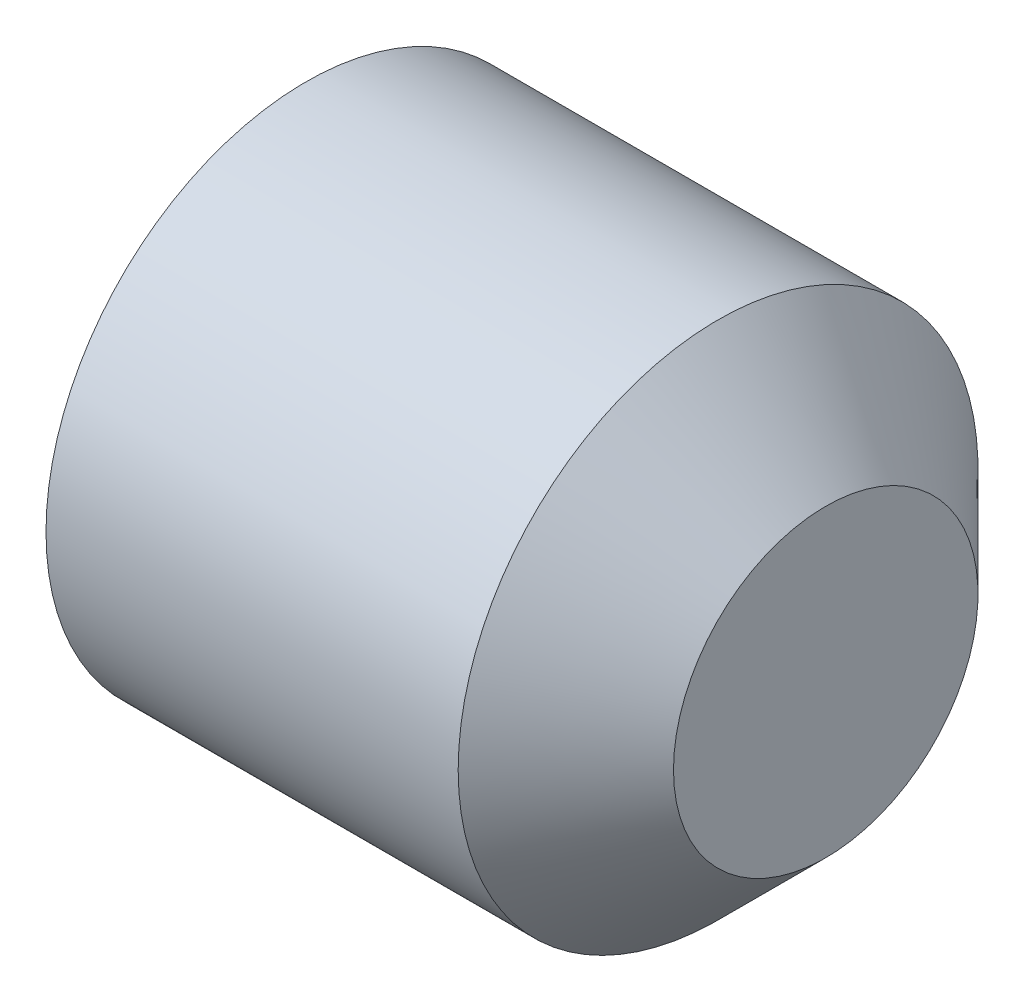
SolidWorks part; units mm, degrees
material "AISI 304"
ref_plane "Front Plane" through (0, 0, 0) normal (0, 0, 1) x (1, 0, 0)
ref_plane "Top Plane" through (0, 0, 0) normal (0, 1, 0) x (1, 0, 0)
ref_plane "Right Plane" through (0, 0, 0) normal (1, 0, 0) x (0, 0, -1)
sketch "Sketch1" plane through (0, 0, 0) normal (0, 0, 1) x (1, 0, 0)
  line L0 (0, 0) -> (105.4919, 0) construction
  line L1 (4, 1.1716) -> (4, 0)
  line L2 (4, 1.1716) -> (3.1716, 2)
  line L3 (3.1716, 2) -> (0, 2)
  line L4 (0, 2) -> (0, 0)
  line L5 (0, 0) -> (4, 0)
  dimension "D1" = 4
  dimension "D2" = 4
  dimension "D3" = 45
  dimension "D4" = 90
revolve "Revolve1" add sketch "Sketch1" angle 360 about L0
sketch "Sketch2" plane through (0, 0, 0) normal (-1, 0, 0) x (0, 0, 1)
  line L1 (-0.5774, 1) -> (-1.1547, 0)
  line L2 (-1.1547, 0) -> (-0.5774, -1)
  line L3 (-0.5774, -1) -> (0.5774, -1)
  line L4 (0.5774, -1) -> (1.1547, 0)
  line L5 (1.1547, 0) -> (0.5774, 1)
  line L6 (0.5774, 1) -> (-0.5774, 1)
  circle A0 centre (0, 0) radius 1 construction
  dimension "D1" = 2
extrude "Cut-Extrude1" cut sketch "Sketch2" against normal blind 1.5
